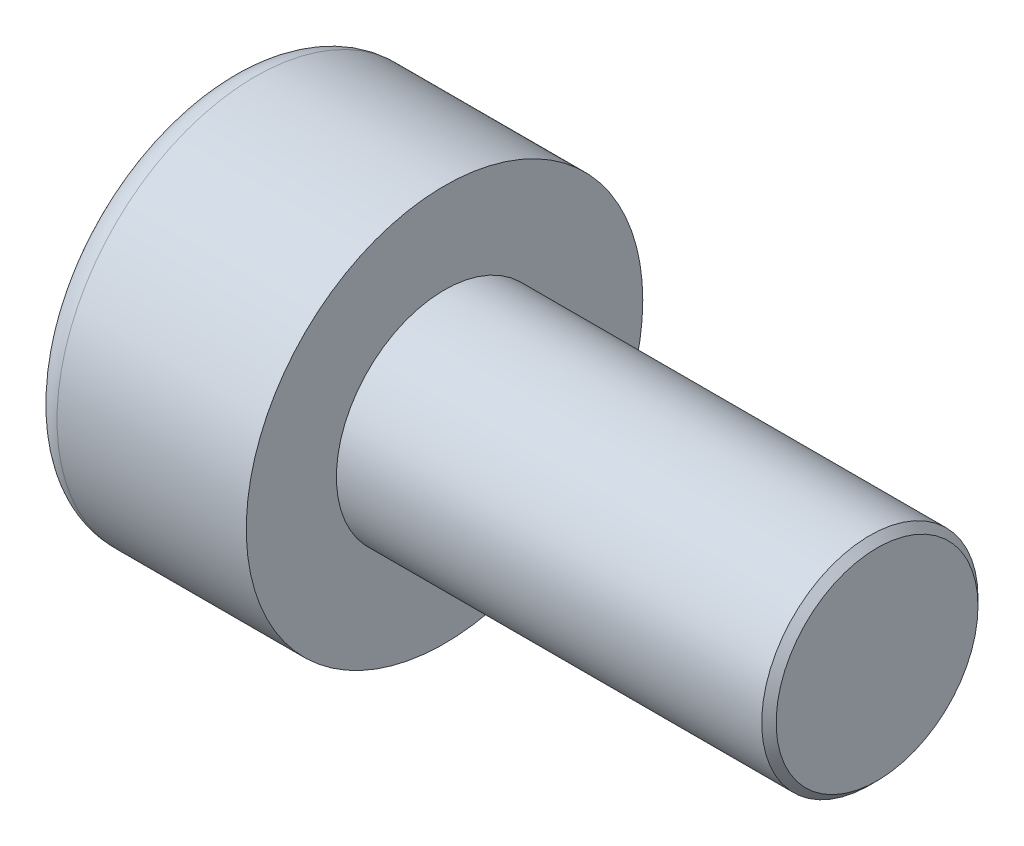
SolidWorks part; units mm, degrees
material "合金钢"
ref_plane "Front" through (0, 0, 0) normal (0, 0, 1) x (1, 0, 0)
ref_plane "Top" through (0, 0, 0) normal (0, 1, 0) x (1, 0, 0)
ref_plane "Right" through (0, 0, 0) normal (1, 0, 0) x (0, 0, -1)
sketch "Sketch1" plane through (0, 0, 0) normal (1, 0, 0) x (0, 0, -1)
  circle A0 centre (0, 0) radius 2.75
  dimension "dk" = 5.5
extrude "BaseHead" add sketch "Sketch1" along normal blind 3
sketch "Sketch2" plane through (3, 0, 0) normal (1, 0, 0) x (0, 0, -1)
  circle A0 centre (0, 0) radius 1.5
  dimension "d" = 3
extrude "BaseBody" add sketch "Sketch2" along normal blind 6
cosmetic thread "ThreadCosmetic1" [suppressed] parameters "b"=6, "D2"=2.459
sketch "Sketch3" plane through (0, 0, 0) normal (1, 0, 0) x (0, 0, -1)
  line L1 (1.4434, 0) -> (0.7217, 1.25)
  line L2 (0.7217, 1.25) -> (-0.7217, 1.25)
  line L3 (-0.7217, 1.25) -> (-1.4434, 0)
  line L4 (-1.4434, 0) -> (-0.7217, -1.25)
  line L5 (-0.7217, -1.25) -> (0.7217, -1.25)
  line L6 (0.7217, -1.25) -> (1.4434, 0)
  circle A0 centre (0, 0) radius 1.25 construction
  dimension "s" = 2.5
  dimension "e" = 2.8868
extrude "HexagonSocket" cut sketch "Sketch3" along normal blind 1.3
sketch "Sketch4" plane through (-4.1961, 0.75, 0) normal (0, 0, 1) x (-1, 0, 0)
  line L0 (-5.4961, 2) -> (-6.2178, 0.75)
  line L2 (-6.2178, 0.75) -> (-5.4961, 0.75)
  line L3 (-5.4961, 0.75) -> (-5.4961, 2)
  line L4 (-5.0351, 0.75) -> (0.839, 0.75) construction
  line L5 (-13.1961, 0.75) -> (-7.1961, 0.75) construction
  line L6 (-7.1961, 0.75) -> (-4.1961, 0.75) construction
  dimension "m" = 60
revolve "Cut-Revolve1" cut sketch "Sketch4" angle 360 about L4
fillet "HeadFillet" [suppressed] radius 0.1
fillet "TopFillet" radius 0.375 1 edges at (0, 0, -2.75)
chamfer "Chamfer1" distance 0.1 angle 45 1 edges at (9, 0, -1.5)
sketch "Sketch5" plane through (0, 0, 0) normal (0, 0, 1) x (1, 0, 0)
  line L0 (8.9, 1.2657) -> (9.0353, 1.5)
  line L1 (9.0353, 1.5) -> (9.0353, 1.7705)
  line L2 (9.0353, 1.7705) -> (8.7648, 1.7705)
  line L3 (8.7648, 1.7705) -> (8.7648, 1.5)
  line L4 (8.7648, 1.5) -> (8.9, 1.2657)
  line L5 (0, 0) -> (7.8886, 0) construction
  line L6 (8.9, -1.5) -> (8.9, 1.5) construction
  dimension "D1" = 3
  dimension "D2" = 0.2705
revolve "Cut-Revolve10" [suppressed] cut sketch "Sketch5" angle 360 about L5
pattern_linear "LPattern10" [suppressed] count 18 spacing 0.3246 along (1, 0, 0)
equation "\"r1@TopFillet\" = \"d@Sketch2\" / 8"
equation "\"D1@Chamfer1\" = \"r@HeadFillet\""
equation "\"D1@Sketch5\" = \"d@Sketch2\""
equation "\"D2@Sketch5\" =  ( \"d@Sketch2\" - \"D2@ThreadCosmetic1\" )  / 2"
equation "\"D3@LPattern10\" = \"D2@Sketch5\" * 1.2"
equation "\"D1@LPattern10\" = \"b@ThreadCosmetic1\" / \"D3@LPattern10\""
